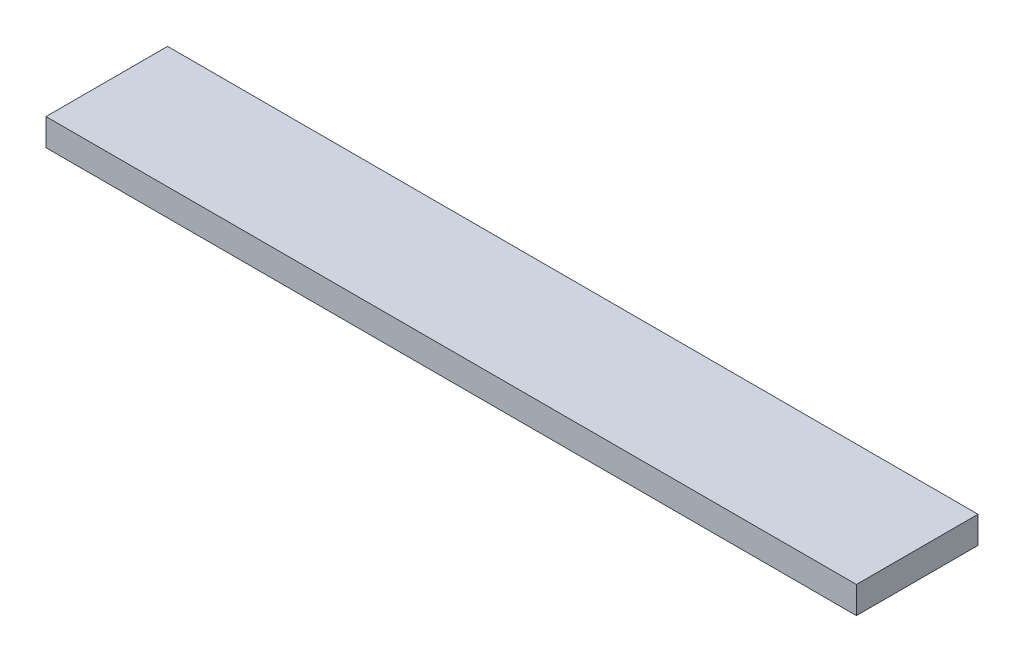
SolidWorks part; units mm, degrees
ref_plane "前视基准面" through (0, 0, 0) normal (0, 0, 1) x (1, 0, 0)
ref_plane "上视基准面" through (0, 0, 0) normal (0, 1, 0) x (1, 0, 0)
ref_plane "右视基准面" through (0, 0, 0) normal (1, 0, 0) x (0, 0, -1)
sketch "草图1" plane through (0, 0, 0) normal (0, 1, 0) x (1, 0, 0)
  line L1 (-150, 22.5) -> (150, 22.5)
  line L2 (-150, 22.5) -> (-150, -22.5)
  line L3 (-150, -22.5) -> (150, -22.5)
  line L4 (150, 22.5) -> (150, -22.5)
  line L5 (-150, 22.5) -> (150, -22.5) construction
  line L6 (-150, -22.5) -> (150, 22.5) construction
  point P0 (0, 0)
  dimension "D1" = 45
  dimension "D2" = 300
extrude "凸台-拉伸1" add sketch "草图1" along normal blind 10
